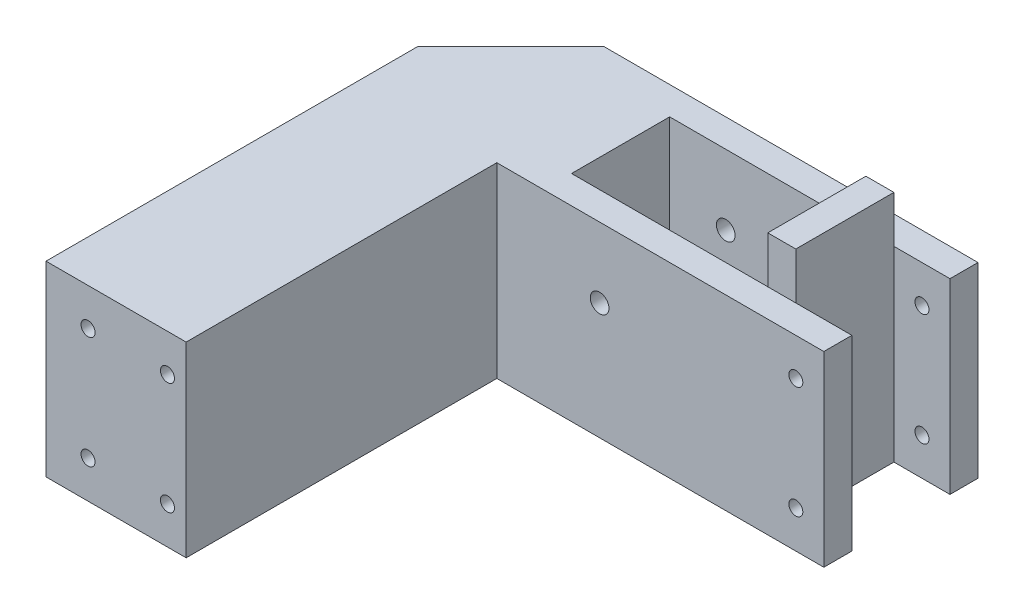
SolidWorks part; units mm, degrees
ref_plane "前视基准面" through (0, 0, 0) normal (0, 0, 1) x (1, 0, 0)
ref_plane "上视基准面" through (0, 0, 0) normal (0, 1, 0) x (1, 0, 0)
ref_plane "右视基准面" through (0, 0, 0) normal (1, 0, 0) x (0, 0, -1)
other "Configuration Table"
sketch "草图1" plane through (0, 0, 0) normal (0, 1, 0) x (1, 0, 0)
  line L1 (0, 0) -> (80, 0)
  line L3 (0, 33) -> (80, 33)
  line L9 (0, 33) -> (0, 0)
  line L10 (80, 33) -> (80, 27)
  line L11 (80, 27) -> (20, 27)
  line L12 (20, 27) -> (20, 6)
  line L13 (20, 6) -> (80, 6)
  line L14 (80, 6) -> (80, 0)
  dimension "D1" = 21
  dimension "D2" = 60
  dimension "D3" = 6
  dimension "D4" = 6
  dimension "D5" = 80
extrude "凸台-拉伸1" add sketch "草图1" along normal blind 40
sketch "草图7" plane through (0, 40, 0) normal (0, 1, 0) x (1, 0, 0)
  line L0 (0, 33) -> (0, 0) construction
  line L1 (20, 5.4804) -> (0, 5.4804)
  line L2 (20, 5.4804) -> (20, 0)
  line L3 (20, 0) -> (0, 0)
  line L4 (0, 5.4804) -> (0, 0)
  line L6 (0, 0) -> (80, 0) construction
  dimension "D1" = 5.4804
  dimension "D2" = 20
sketch "草图8" plane through (0, 0, -33) normal (0, 0, -1) x (-1, 0, 0)
  line L0 (-80, 40) -> (-80, 0) construction
  line L1 (-74, 32) -> (-6, 32) construction
  line L2 (-74, 32) -> (-74, 8) construction
  line L3 (-74, 8) -> (-6, 8) construction
  line L4 (-6, 32) -> (-6, 8) construction
  line L5 (-80, 40) -> (0, 40) construction
  circle A0 centre (-74, 8) radius 1.5
  circle A1 centre (-74, 32) radius 1.5
  circle A2 centre (-6, 32) radius 1.5
  circle A3 centre (-6, 8) radius 1.5
  dimension "D4" = 3
  dimension "D1" = 68
  dimension "D2" = 24
  dimension "D3" = 6
  dimension "D5" = 8
extrude "切除-拉伸2" cut sketch "草图8" against normal through all
sketch "草图12" plane through (0, 0, 0) normal (0, 0, 1) x (1, 0, 0)
  line L0 (0, 0) -> (80, 0) construction
  line L1 (10, 0) -> (-20, 0)
  line L2 (10, 0) -> (10, 40)
  line L3 (10, 40) -> (-20, 40)
  line L4 (-20, 0) -> (-20, 40)
  line L5 (0, 40) -> (80, 40) construction
  line L6 (0, 40) -> (0, 0) construction
  line L7 (-11, 32) -> (6, 32) construction
  line L9 (6, 8) -> (-11, 8) construction
  circle A0 centre (-11, 32) radius 1.5
  circle A1 centre (-11, 8) radius 1.5
  circle A2 centre (6, 8) radius 1.5 construction
  circle A3 centre (6, 32) radius 1.5 construction
  circle A4 centre (6, 8) radius 1.5
  circle A5 centre (6, 32) radius 1.5
  dimension "D3" = 3
  dimension "D4" = 3
  dimension "D1" = 30
  dimension "D2" = 20
  dimension "D5" = 17
extrude "凸台-拉伸7" add sketch "草图12" along normal blind 66.5 and the other way up to surface other way up to face at (4.5, 8, -33)
sketch "草图14" plane through (0, 40, 0) normal (0, 1, 0) x (1, 0, 0)
  line L0 (-20, 33) -> (0, 33)
  line L1 (80, 33) -> (-20, 33) construction
  line L2 (0, 33) -> (-20, 13)
  line L3 (-20, 33) -> (-20, -66.5) construction
  line L4 (-20, 13) -> (-20, 33)
  dimension "D1" = 20
  dimension "D2" = 20
extrude "切除-拉伸3" cut sketch "草图14" against normal through all
sketch "草图15" plane through (0, 0, 66.5) normal (0, 0, 1) x (1, 0, 0)
  circle A0 centre (-11, 32) radius 3.5
  circle A1 centre (-11, 8) radius 3.5
  dimension "D1" = 7
  dimension "D2" = 7
extrude "切除-拉伸4" cut sketch "草图15" against normal through all from offset 50 offset against normal yes
sketch "草图16" plane through (0, 40, 0) normal (0, 1, 0) x (1, 0, 0)
  line L0 (20, 27) -> (80, 27) construction
  line L1 (62, 27) -> (68, 27)
  line L2 (62, 27) -> (62, 6)
  line L3 (62, 6) -> (68, 6)
  line L4 (68, 27) -> (68, 6)
  line L5 (80, 6) -> (20, 6) construction
  line L6 (20, 6) -> (20, 27) construction
  dimension "D1" = 6
  dimension "D2" = 42
extrude "凸台-拉伸9" add sketch "草图16" along normal blind 10 and the other way up to surface other way up to face at (30.9091, 0, -1.0909)
sketch "草图17" plane through (0, 0, 0) normal (0, 0, 1) x (1, 0, 0)
  line L0 (10, 40) -> (10, 0) construction
  line L2 (10, 0) -> (80, 0) construction
  circle A0 centre (32, 25) radius 2
  dimension "D3" = 4
  dimension "D1" = 22
  dimension "D2" = 25
extrude "切除-拉伸5" cut sketch "草图17" against normal through all
